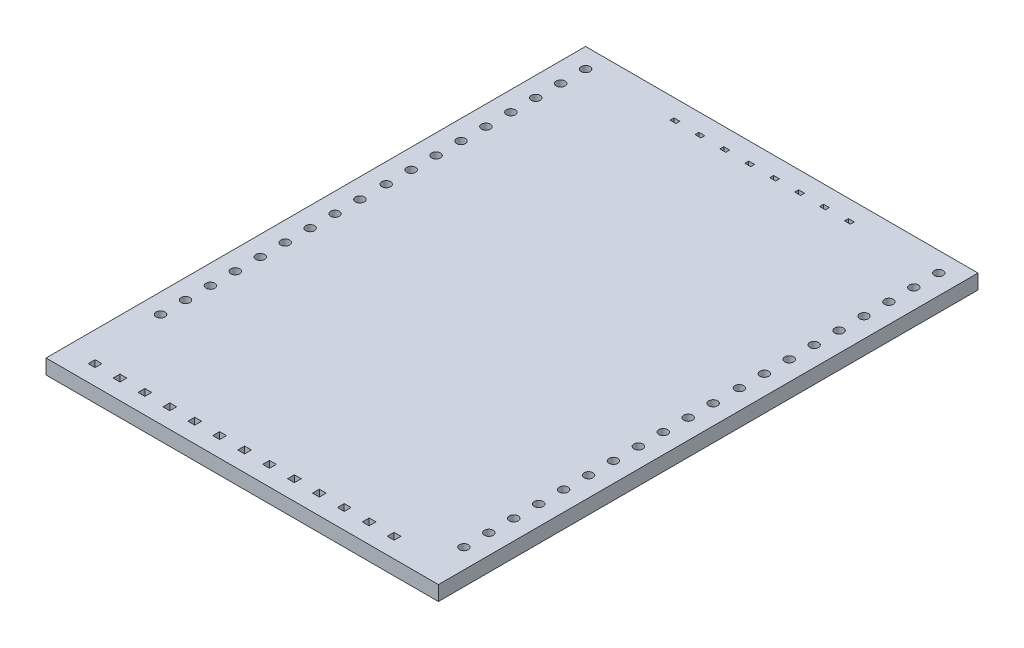
SolidWorks part; units mm, degrees
ref_plane "Front" through (0, 0, 0) normal (0, 0, 1) x (1, 0, 0)
ref_plane "Top" through (0, 0, 0) normal (0, 1, 0) x (1, 0, 0)
ref_plane "Right" through (0, 0, 0) normal (1, 0, 0) x (0, 0, -1)
sketch "Эскиз1" plane through (0, 0, 0) normal (0, 1, 0) x (1, 0, 0)
  line L1 (-20, 27.5) -> (20, 27.5)
  line L2 (-20, 27.5) -> (-20, -27.5)
  line L3 (-20, -27.5) -> (20, -27.5)
  line L4 (20, 27.5) -> (20, -27.5)
  line L5 (-20, 27.5) -> (20, -27.5) construction
  line L6 (-20, -27.5) -> (20, 27.5) construction
  point P0 (0, 0)
extrude "Бобышка-Вытянуть1" add sketch "Эскиз1" along normal blind 1.5
sketch "Эскиз2" plane through (0, 1.5, 0) normal (0, 1, 0) x (1, 0, 0)
  line L0 (-20, -27.5) -> (-20, -25.5) construction
  line L1 (-20, 27.5) -> (-20, -27.5) construction
  line L2 (20, -27.5) -> (20, -22.9) construction
  line L3 (-14.81, -25.15) -> (-14.11, -25.15)
  line L4 (-17.35, -25.15) -> (-16.65, -25.15)
  line L5 (-17.35, -25.15) -> (-17.35, -25.85)
  line L6 (-17.35, -25.85) -> (-16.65, -25.85)
  line L7 (-16.65, -25.15) -> (-16.65, -25.85)
  line L8 (-17.35, -25.15) -> (-16.65, -25.85) construction
  line L9 (-17.35, -25.85) -> (-16.65, -25.15) construction
  line L10 (-14.81, -25.15) -> (-14.81, -25.85)
  line L11 (-14.81, -25.85) -> (-14.11, -25.85)
  line L12 (-14.11, -25.15) -> (-14.11, -25.85)
  line L13 (-14.81, -25.15) -> (-14.11, -25.85) construction
  line L14 (-14.81, -25.85) -> (-14.11, -25.15) construction
  line L15 (-12.27, -25.15) -> (-11.57, -25.15)
  line L16 (-12.27, -25.15) -> (-12.27, -25.85)
  line L17 (-12.27, -25.85) -> (-11.57, -25.85)
  line L18 (-11.57, -25.15) -> (-11.57, -25.85)
  line L19 (-12.27, -25.15) -> (-11.57, -25.85) construction
  line L20 (-12.27, -25.85) -> (-11.57, -25.15) construction
  line L21 (-9.73, -25.15) -> (-9.03, -25.15)
  line L22 (-9.73, -25.15) -> (-9.73, -25.85)
  line L23 (-9.73, -25.85) -> (-9.03, -25.85)
  line L24 (-9.03, -25.15) -> (-9.03, -25.85)
  line L25 (-9.73, -25.15) -> (-9.03, -25.85) construction
  line L26 (-9.73, -25.85) -> (-9.03, -25.15) construction
  line L27 (-7.19, -25.15) -> (-6.49, -25.15)
  line L28 (-7.19, -25.15) -> (-7.19, -25.85)
  line L29 (-7.19, -25.85) -> (-6.49, -25.85)
  line L30 (-6.49, -25.15) -> (-6.49, -25.85)
  line L31 (-7.19, -25.15) -> (-6.49, -25.85) construction
  line L32 (-7.19, -25.85) -> (-6.49, -25.15) construction
  line L33 (-4.65, -25.15) -> (-3.95, -25.15)
  line L34 (-4.65, -25.15) -> (-4.65, -25.85)
  line L35 (-4.65, -25.85) -> (-3.95, -25.85)
  line L36 (-3.95, -25.15) -> (-3.95, -25.85)
  line L37 (-4.65, -25.15) -> (-3.95, -25.85) construction
  line L38 (-4.65, -25.85) -> (-3.95, -25.15) construction
  line L39 (-2.11, -25.15) -> (-1.41, -25.15)
  line L40 (-2.11, -25.15) -> (-2.11, -25.85)
  line L41 (-2.11, -25.85) -> (-1.41, -25.85)
  line L42 (-1.41, -25.15) -> (-1.41, -25.85)
  line L43 (-2.11, -25.15) -> (-1.41, -25.85) construction
  line L44 (-2.11, -25.85) -> (-1.41, -25.15) construction
  line L45 (0.43, -25.15) -> (1.13, -25.15)
  line L46 (0.43, -25.15) -> (0.43, -25.85)
  line L47 (0.43, -25.85) -> (1.13, -25.85)
  line L48 (1.13, -25.15) -> (1.13, -25.85)
  line L49 (0.43, -25.15) -> (1.13, -25.85) construction
  line L50 (0.43, -25.85) -> (1.13, -25.15) construction
  line L51 (2.97, -25.15) -> (3.67, -25.15)
  line L52 (2.97, -25.15) -> (2.97, -25.85)
  line L53 (2.97, -25.85) -> (3.67, -25.85)
  line L54 (3.67, -25.15) -> (3.67, -25.85)
  line L55 (2.97, -25.15) -> (3.67, -25.85) construction
  line L56 (2.97, -25.85) -> (3.67, -25.15) construction
  line L57 (5.51, -25.15) -> (6.21, -25.15)
  line L58 (5.51, -25.15) -> (5.51, -25.85)
  line L59 (5.51, -25.85) -> (6.21, -25.85)
  line L60 (6.21, -25.15) -> (6.21, -25.85)
  line L61 (5.51, -25.15) -> (6.21, -25.85) construction
  line L62 (5.51, -25.85) -> (6.21, -25.15) construction
  line L63 (8.05, -25.15) -> (8.75, -25.15)
  line L64 (8.05, -25.15) -> (8.05, -25.85)
  line L65 (8.05, -25.85) -> (8.75, -25.85)
  line L66 (8.75, -25.15) -> (8.75, -25.85)
  line L67 (8.05, -25.15) -> (8.75, -25.85) construction
  line L68 (8.05, -25.85) -> (8.75, -25.15) construction
  line L69 (10.59, -25.15) -> (11.29, -25.15)
  line L70 (10.59, -25.15) -> (10.59, -25.85)
  line L71 (10.59, -25.85) -> (11.29, -25.85)
  line L72 (11.29, -25.15) -> (11.29, -25.85)
  line L73 (10.59, -25.15) -> (11.29, -25.85) construction
  line L74 (10.59, -25.85) -> (11.29, -25.15) construction
  line L75 (13.13, -25.15) -> (13.83, -25.15)
  line L76 (13.13, -25.15) -> (13.13, -25.85)
  line L77 (13.13, -25.85) -> (13.83, -25.85)
  line L78 (13.83, -25.15) -> (13.83, -25.85)
  line L79 (13.13, -25.15) -> (13.83, -25.85) construction
  line L80 (13.13, -25.85) -> (13.83, -25.15) construction
  line L81 (20, -27.5) -> (20, 27.5) construction
  line L82 (20, -22.9) -> (18, -22.9) construction
  line L83 (0, 27.5) -> (0, -27.5) construction
  line L84 (20, 27.5) -> (-20, 27.5) construction
  line L85 (-20, -27.5) -> (20, -27.5) construction
  line L86 (20, -27.5) -> (20, 5.18) construction
  line L87 (20, 5.18) -> (18, 5.18) construction
  line L88 (20, 27.5) -> (20, 25.5) construction
  line L89 (-20, 27.5) -> (-20, 25.5) construction
  line L90 (-20, 25.5) -> (8.89, 25.5) construction
  line L91 (6.05, 25.7) -> (6.65, 25.7)
  line L92 (8.59, 25.7) -> (9.19, 25.7)
  line L93 (8.59, 25.7) -> (8.59, 25.3)
  line L94 (8.59, 25.3) -> (9.19, 25.3)
  line L95 (9.19, 25.7) -> (9.19, 25.3)
  line L96 (8.59, 25.7) -> (9.19, 25.3) construction
  line L97 (8.59, 25.3) -> (9.19, 25.7) construction
  line L98 (6.05, 25.7) -> (6.05, 25.3)
  line L99 (6.05, 25.3) -> (6.65, 25.3)
  line L100 (6.65, 25.7) -> (6.65, 25.3)
  line L101 (6.05, 25.7) -> (6.65, 25.3) construction
  line L102 (6.05, 25.3) -> (6.65, 25.7) construction
  line L103 (3.51, 25.7) -> (4.11, 25.7)
  line L104 (3.51, 25.7) -> (3.51, 25.3)
  line L105 (3.51, 25.3) -> (4.11, 25.3)
  line L106 (4.11, 25.7) -> (4.11, 25.3)
  line L107 (3.51, 25.7) -> (4.11, 25.3) construction
  line L108 (3.51, 25.3) -> (4.11, 25.7) construction
  line L109 (0.97, 25.7) -> (1.57, 25.7)
  line L110 (0.97, 25.7) -> (0.97, 25.3)
  line L111 (0.97, 25.3) -> (1.57, 25.3)
  line L112 (1.57, 25.7) -> (1.57, 25.3)
  line L113 (0.97, 25.7) -> (1.57, 25.3) construction
  line L114 (0.97, 25.3) -> (1.57, 25.7) construction
  line L115 (-1.57, 25.7) -> (-0.97, 25.7)
  line L116 (-1.57, 25.7) -> (-1.57, 25.3)
  line L117 (-1.57, 25.3) -> (-0.97, 25.3)
  line L118 (-0.97, 25.7) -> (-0.97, 25.3)
  line L119 (-1.57, 25.7) -> (-0.97, 25.3) construction
  line L120 (-1.57, 25.3) -> (-0.97, 25.7) construction
  line L121 (-4.11, 25.7) -> (-3.51, 25.7)
  line L122 (-4.11, 25.7) -> (-4.11, 25.3)
  line L123 (-4.11, 25.3) -> (-3.51, 25.3)
  line L124 (-3.51, 25.7) -> (-3.51, 25.3)
  line L125 (-4.11, 25.7) -> (-3.51, 25.3) construction
  line L126 (-4.11, 25.3) -> (-3.51, 25.7) construction
  line L127 (-6.65, 25.7) -> (-6.05, 25.7)
  line L128 (-6.65, 25.7) -> (-6.65, 25.3)
  line L129 (-6.65, 25.3) -> (-6.05, 25.3)
  line L130 (-6.05, 25.7) -> (-6.05, 25.3)
  line L131 (-6.65, 25.7) -> (-6.05, 25.3) construction
  line L132 (-6.65, 25.3) -> (-6.05, 25.7) construction
  line L133 (-9.19, 25.7) -> (-8.59, 25.7)
  line L134 (-9.19, 25.7) -> (-9.19, 25.3)
  line L135 (-9.19, 25.3) -> (-8.59, 25.3)
  line L136 (-8.59, 25.7) -> (-8.59, 25.3)
  line L137 (-9.19, 25.7) -> (-8.59, 25.3) construction
  line L138 (-9.19, 25.3) -> (-8.59, 25.7) construction
  line L139 (-1.27, 25.5) -> (0, 25.5) construction
  circle A0 centre (18, -22.9) radius 0.45
  circle A1 centre (18, -20.36) radius 0.45
  circle A2 centre (18, -17.82) radius 0.45
  circle A3 centre (18, -15.28) radius 0.45
  circle A4 centre (18, -12.74) radius 0.45
  circle A5 centre (18, -10.2) radius 0.45
  circle A6 centre (18, -7.66) radius 0.45
  circle A7 centre (18, -5.12) radius 0.45
  circle A8 centre (18, -2.58) radius 0.45
  circle A9 centre (18, -0.04) radius 0.45
  circle A10 centre (18, 2.5) radius 0.45
  circle A11 centre (-18, 2.5) radius 0.45
  circle A12 centre (-18, -0.04) radius 0.45
  circle A13 centre (-18, -2.58) radius 0.45
  circle A14 centre (-18, -5.12) radius 0.45
  circle A15 centre (-18, -7.66) radius 0.45
  circle A16 centre (-18, -10.2) radius 0.45
  circle A17 centre (-18, -12.74) radius 0.45
  circle A18 centre (-18, -15.28) radius 0.45
  circle A19 centre (-18, -17.82) radius 0.45
  circle A20 centre (18, 5.18) radius 0.45
  circle A21 centre (18, 7.72) radius 0.45
  circle A22 centre (18, 10.26) radius 0.45
  circle A23 centre (18, 12.8) radius 0.45
  circle A24 centre (18, 15.34) radius 0.45
  circle A25 centre (18, 17.88) radius 0.45
  circle A26 centre (18, 20.42) radius 0.45
  circle A27 centre (18, 22.96) radius 0.45
  circle A28 centre (18, 25.5) radius 0.45
  circle A29 centre (-18, 25.5) radius 0.45
  circle A30 centre (-18, 22.96) radius 0.45
  circle A31 centre (-18, 20.42) radius 0.45
  circle A32 centre (-18, 17.88) radius 0.45
  circle A33 centre (-18, 15.34) radius 0.45
  circle A34 centre (-18, 12.8) radius 0.45
  circle A35 centre (-18, 10.26) radius 0.45
  circle A36 centre (-18, 7.72) radius 0.45
  circle A37 centre (-18, 5.18) radius 0.45
  dimension "D2" = 11
  dimension "D3" = 9
  dimension "D1" = 13
  dimension "D4" = 8
extrude "Вырез-Вытянуть1" cut sketch "Эскиз2" against normal through all
